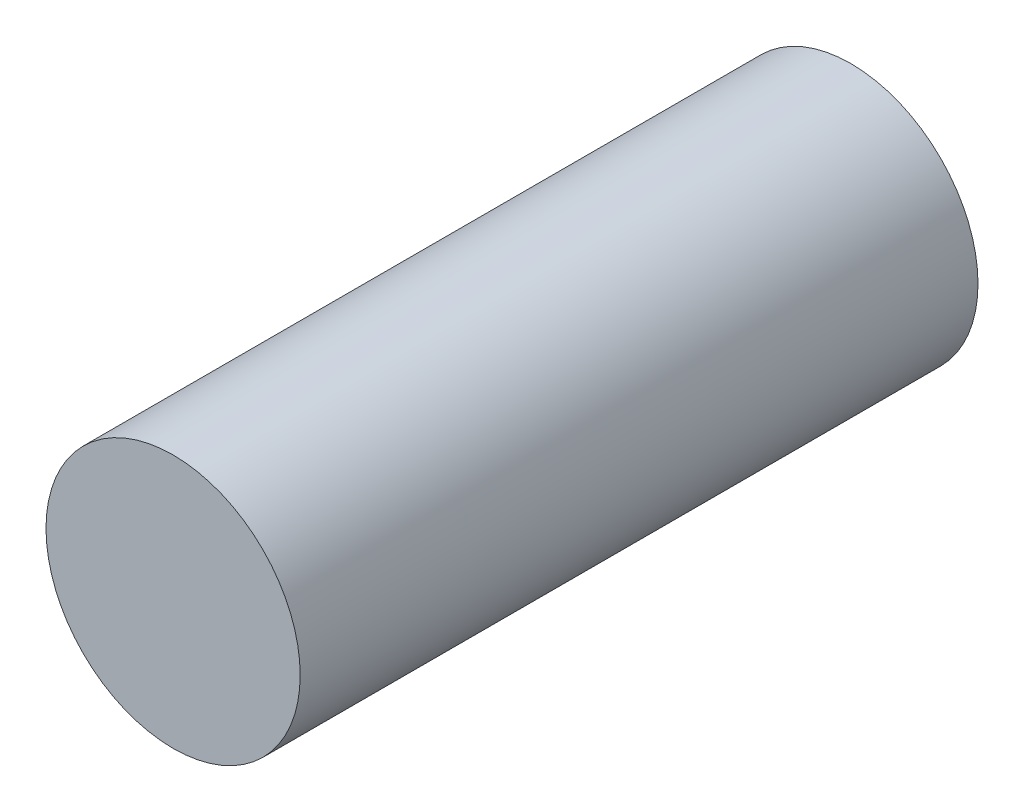
SolidWorks part; units mm, degrees
ref_plane "前视基准面" through (0, 0, 0) normal (0, 0, 1) x (1, 0, 0)
ref_plane "上视基准面" through (0, 0, 0) normal (0, 1, 0) x (1, 0, 0)
ref_plane "右视基准面" through (0, 0, 0) normal (1, 0, 0) x (0, 0, -1)
other "Configuration Table"
sketch "草图1" plane through (0, 0, 0) normal (0, 0, 1) x (1, 0, 0)
  circle A0 centre (0, 0) radius 150
extrude "凸台-拉伸1" add sketch "草图1" along normal blind 800
